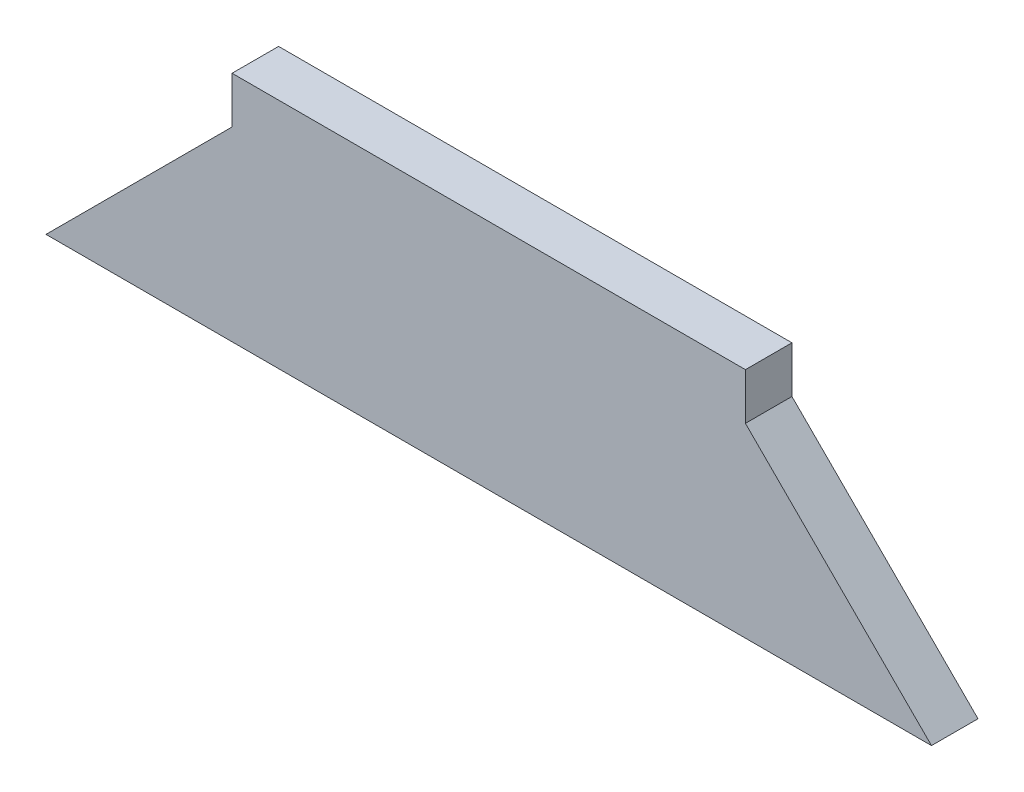
SolidWorks part; units mm, degrees
ref_plane "Alzado" through (0, 0, 0) normal (0, 0, 1) x (1, 0, 0)
ref_plane "Planta" through (0, 0, 0) normal (0, 1, 0) x (1, 0, 0)
ref_plane "Vista lateral" through (0, 0, 0) normal (1, 0, 0) x (0, 0, -1)
sketch "Croquis1" plane through (0, 0, 0) normal (0, 0, 1) x (1, 0, 0)
  line L0 (-16.555, 7) -> (-28.555, -5)
  line L2 (-16.555, 7) -> (-16.555, 10)
  line L3 (-16.555, 10) -> (16.555, 10)
  line L4 (16.555, 7) -> (16.555, 10)
  line L13 (-28.555, -5) -> (28.555, -5)
  line L14 (28.555, -5) -> (16.555, 7)
  point P0 (0, 0)
  point P6 (0, 10)
  dimension "D1" = 15
  dimension "D2" = 33.11
extrude "Saliente-Extruir1" add sketch "Croquis1" along normal blind 3
